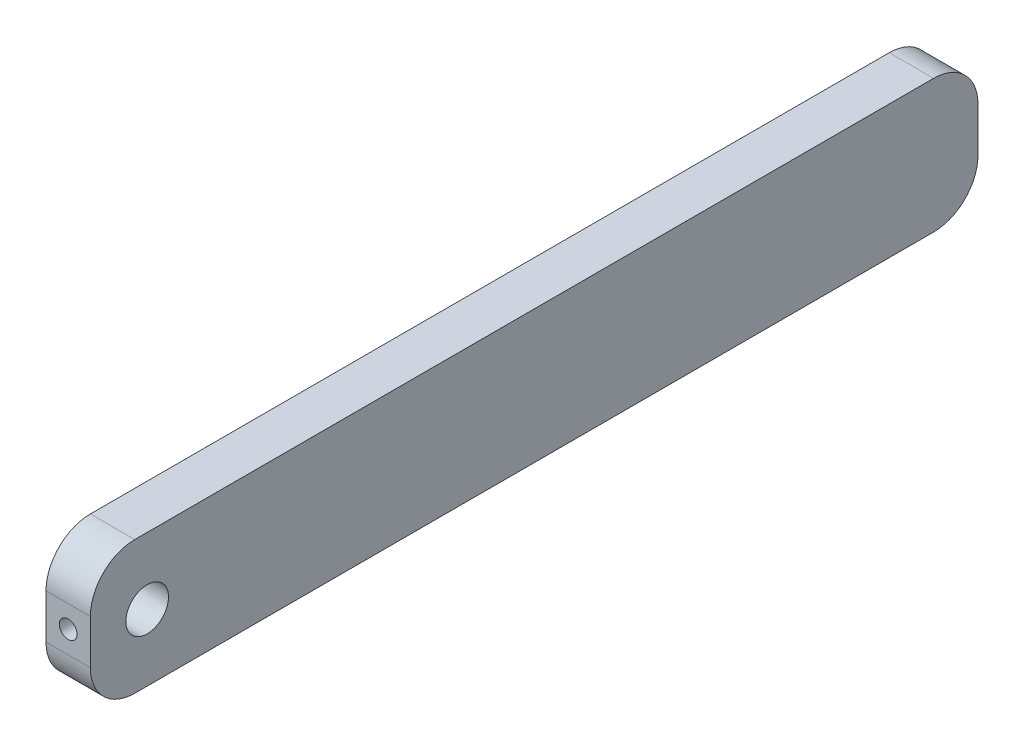
SolidWorks part; units mm, degrees
ref_plane "前视基准面" through (0, 0, 0) normal (0, 0, 1) x (1, 0, 0)
ref_plane "上视基准面" through (0, 0, 0) normal (0, 1, 0) x (1, 0, 0)
ref_plane "右视基准面" through (0, 0, 0) normal (1, 0, 0) x (0, 0, -1)
other "Configuration Table"
sketch "草图1" plane through (0, 0, 0) normal (1, 0, 0) x (0, 0, -1)
  line L1 (0, 0) -> (100, 0)
  line L2 (0, 0) -> (0, 15)
  line L3 (0, 15) -> (100, 15)
  line L4 (100, 0) -> (100, 15)
  dimension "D1" = 15
  dimension "D2" = 100
extrude "凸台-拉伸1" add sketch "草图1" along normal blind 5
sketch "草图2" plane through (5, 0, 0) normal (1, 0, 0) x (0, 0, -1)
  line L0 (0, 7.5) -> (24.1805, 7.5) construction
  line L1 (0, 15) -> (0, 0) construction
  circle A0 centre (6.4, 7.5) radius 2.4
  dimension "D1" = 4.8
  dimension "D2" = 6.4
extrude "切除-拉伸1" cut sketch "草图2" against normal blind 5
fillet "圆角1" radius 5 4 edges at (2.5, 0, -100) (2.5, 15, -100) (2.5, 0, 0) (2.5, 15, 0)
sketch "草图4" plane through (0, 0, 0) normal (0, 0, 1) x (1, 0, 0)
  line L0 (0, 7.5) -> (5, 7.5) construction
  line L1 (0, 10) -> (0, 5) construction
  line L2 (5, 10) -> (5, 5) construction
  circle A0 centre (2.5, 7.5) radius 1
  dimension "D1" = 2
extrude "切除-拉伸2" cut sketch "草图4" against normal blind 7 contours A0
